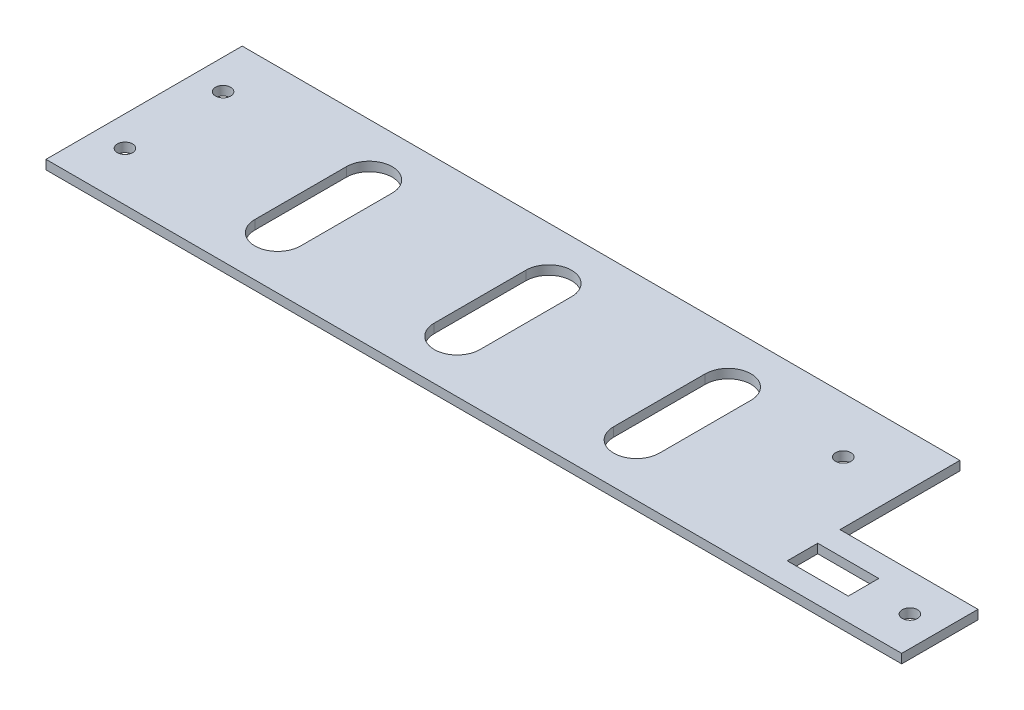
SolidWorks part; units mm, degrees
material "Custom Plastic"
ref_plane "Plan de face" through (0, 0, 0) normal (0, 0, 1) x (1, 0, 0)
ref_plane "Plan de dessus" through (0, 0, 0) normal (0, 1, 0) x (1, 0, 0)
ref_plane "Plan de droite" through (0, 0, 0) normal (1, 0, 0) x (0, 0, -1)
sketch "Esquisse1" plane through (0, 0, 0) normal (0, 1, 0) x (1, 0, 0)
  line L1 (-170.0285, 28.77) -> (110.2715, 28.77) construction
  line L2 (-170.0285, 28.77) -> (-170.0285, -35.5) construction
  line L3 (-170.0285, -35.5) -> (110.2715, -35.5) construction
  line L4 (110.2715, 28.77) -> (110.2715, -35.5) construction
  line L5 (-170.0285, 28.77) -> (110.2715, -35.5) construction
  line L6 (-170.0285, -35.5) -> (110.2715, 28.77) construction
  line L7 (110.2715, 18.77) -> (110.2715, -23) construction
  line L9 (-170.0285, 18.77) -> (-170.0285, -23)
  line L10 (-170.0285, 18.77) -> (-160.0285, 18.77) construction
  line L12 (-170.0285, -35.5) -> (110.2715, -35.5)
  line L13 (110.4715, -10.5) -> (110.4715, -35.5) construction
  line L14 (-160.0285, 28.77) -> (-160.0285, 18.77) construction
  line L15 (65.0578, -2.5147) -> (65.0578, -50002.5147) construction
  line L16 (-170.0285, -23) -> (-160.0285, -23) construction
  line L17 (58.3078, 10.635) -> (45.0078, 10.635) construction
  line L18 (-170.2285, -35.5) -> (119.7715, -35.5) construction
  line L19 (-170.0285, 18.77) -> (110.2715, 18.77) construction
  line L21 (110.2715, -23) -> (-170.0285, -23) construction
  line L26 (100.4715, -46.7393) -> (100.4715, -50046.7393) construction
  line L28 (65.0578, 28.77) -> (65.0578, -10.5)
  line L30 (-170.0285, -23) -> (-170.0285, -35.5)
  line L33 (-170.0285, 28.77) -> (-170.0285, 18.77)
  line L34 (-170.0285, 28.77) -> (65.0578, 28.77)
  line L36 (65.0578, -10.5) -> (110.2715, -10.5)
  line L37 (110.2715, -10.5) -> (110.2715, -35.5)
  line L39 (-170.2285, -35.5) -> (-170.2285, -38.5) construction
  line L40 (-170.0285, -35.5) -> (-170.2285, -35.5) construction
  line L41 (110.2715, -35.5) -> (110.4715, -35.5) construction
  line L47 (65.0578, -10.5) -> (119.7715, -10.5) construction
  line L52 (65.0578, 28.77) -> (68.0578, 28.77) construction
  circle A12 centre (100.4715, -23) radius 2.5
  circle A17 centre (-160.2285, -19.4325) radius 2.5
  circle A18 centre (-160.2285, 12.7025) radius 2.5
  circle A19 centre (58.3078, 10.635) radius 2.5 construction
  circle A20 centre (-160.2285, 12.7025) radius 2.5 construction
  circle A21 centre (58.3078, 10.635) radius 2.5 construction
  circle A22 centre (-160.2285, -19.4325) radius 2.5 construction
  circle A23 centre (100.4715, -23) radius 2.5 construction
  circle A24 centre (45.0078, 10.635) radius 2.5
  point P4 (-29.8785, -3.365)
  dimension "D3" = 10
  dimension "D4" = 13.3
  dimension "D7" = 5
  dimension "D1" = 3
  dimension "D2" = 0.2
  dimension "D8" = 0.2
extrude "Boss.-Extru.1" add sketch "Esquisse1" along normal blind 3
sketch "Esquisse2" plane through (0, 3, 0) normal (0, 1, 0) x (1, 0, 0)
  line L0 (-170.0285, 28.77) -> (-170.0285, 38.77) construction
  line L1 (-170.0285, 38.77) -> (-52.4853, 38.77) construction
  line L2 (65.0578, 38.77) -> (65.0578, 28.77) construction
  line L3 (65.0578, -3.365) -> (80.0824, -3.365) construction
  line L4 (100.4715, -23) -> (117.6885, -23) construction
  line L5 (-170.0285, 28.77) -> (-170.0285, -35.5) construction
  line L6 (-52.4853, 38.77) -> (65.0578, 38.77) construction
  line L7 (-111.2569, 38.77) -> (-111.2569, 50038.77) construction
  line L8 (-52.4853, 38.77) -> (-52.4853, 50038.77) construction
  line L9 (6.2862, 38.77) -> (6.2862, 50038.77) construction
  line L10 (-118.7569, 11.635) -> (-118.7569, -18.365)
  line L11 (-103.7569, -18.365) -> (-103.7569, 11.635)
  line L12 (-118.7569, 11.635) -> (-103.7569, 11.635) construction
  line L13 (-103.7569, -18.365) -> (-118.7569, -18.365) construction
  line L14 (-118.7569, -3.365) -> (-103.7569, -3.365) construction
  line L15 (-59.9853, 11.635) -> (-59.9853, -18.365)
  line L16 (-44.9853, -18.365) -> (-44.9853, 11.635)
  line L17 (-59.9853, 11.635) -> (-44.9853, 11.635) construction
  line L18 (-44.9853, -18.365) -> (-59.9853, -18.365) construction
  line L19 (-59.9853, -3.365) -> (-44.9853, -3.365) construction
  line L20 (-1.2138, 11.635) -> (-1.2138, -18.365)
  line L21 (13.7862, -18.365) -> (13.7862, 11.635)
  line L22 (-1.2138, 11.635) -> (13.7862, 11.635) construction
  line L23 (13.7862, -18.365) -> (-1.2138, -18.365) construction
  line L24 (-1.2138, -3.365) -> (13.7862, -3.365) construction
  line L25 (85.2715, -23) -> (85.2715, -50023) construction
  line L26 (110.2715, -35.5) -> (110.2715, -10.5) construction
  line L27 (85.2715, -18) -> (65.2715, -18)
  line L28 (65.2715, -18) -> (65.2715, -28)
  line L29 (65.2715, -28) -> (85.2715, -28)
  line L30 (85.2715, -28) -> (85.2715, -18)
  arc A0 (-103.7569, 11.635) -> (-118.7569, 11.635) centre (-111.2569, 11.635) ccw
  arc A1 (-103.7569, -18.365) -> (-118.7569, -18.365) centre (-111.2569, -18.365) cw
  arc A2 (-44.9853, 11.635) -> (-59.9853, 11.635) centre (-52.4853, 11.635) ccw
  arc A3 (-44.9853, -18.365) -> (-59.9853, -18.365) centre (-52.4853, -18.365) cw
  arc A4 (13.7862, 11.635) -> (-1.2138, 11.635) centre (6.2862, 11.635) ccw
  arc A5 (13.7862, -18.365) -> (-1.2138, -18.365) centre (6.2862, -18.365) cw
  point P7 (-170.0285, -3.365)
  point P8 (-111.2569, 38.77)
  point P13 (6.2862, 38.77)
  point P26 (-111.2569, -3.365)
  point P30 (100.4715, -23)
  point P37 (-52.4853, -3.365)
  point P46 (6.2862, -3.365)
  point P58 (65.2715, -23)
  dimension "D1" = 10
  dimension "D2" = 15
  dimension "D3" = 30
  dimension "D4" = 25
  dimension "D5" = 10
  dimension "D6" = 20
extrude "Enlèv. mat.-Extru.1" cut sketch "Esquisse2" against normal through all
